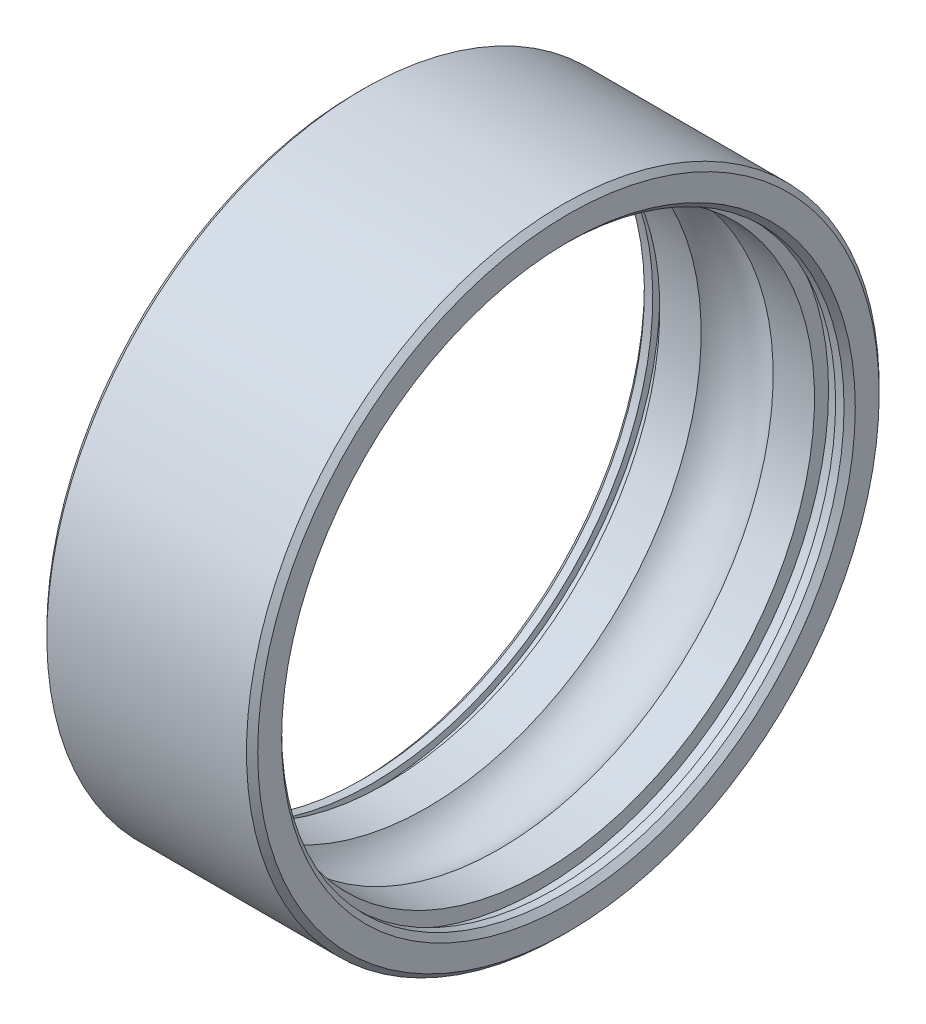
SolidWorks part; units mm, degrees
ref_plane "Front" through (0, 0, 0) normal (0, 0, 1) x (1, 0, 0)
ref_plane "Top" through (0, 0, 0) normal (0, 1, 0) x (1, 0, 0)
ref_plane "Right" through (0, 0, 0) normal (1, 0, 0) x (0, 0, -1)
sketch "Sketch1" plane through (0, 0, 0) normal (0, 0, 1) x (1, 0, 0)
  line L0 (-6.429, 0) -> (6.429, 0) construction
  line L1 (-1.5, -2.5) -> (1.5, -2.5) construction
  line L2 (-1.1, -3.9) -> (-0.5123, -3.9)
  line L3 (-1.5, -4) -> (-1.5, -4.5)
  line L4 (-1.5, -4.5) -> (1.5, -4.5)
  line L5 (1.5, -4) -> (1.5, -4.5)
  line L6 (0, -2.5) -> (0, -4.5) construction
  line L7 (-1.5, -3.1) -> (1.5, -3.1) construction
  line L8 (-1.1, -3.9) -> (-1.1, -4.1)
  line L9 (-1.1, -4.1) -> (-1.3, -4.1)
  line L10 (-1.3, -4.1) -> (-1.3, -4)
  line L11 (-1.3, -4) -> (-1.5, -4)
  line L12 (1.3, -4) -> (1.5, -4)
  line L13 (1.3, -4.1) -> (1.3, -4)
  line L14 (1.1, -4.1) -> (1.3, -4.1)
  line L15 (1.1, -3.9) -> (1.1, -4.1)
  line L16 (0.5123, -3.9) -> (1.1, -3.9)
  circle A0 centre (0, -3.5) radius 0.65 construction
  arc A1 (-0.5123, -3.9) -> (0.5123, -3.9) centre (0, -3.5) ccw
  point P13 (0, -3.5)
  point P15 (-1.3, -4.05)
  point P26 (0, 0)
  point P30 (0, -3.1)
  dimension "D3" = 1.3
  dimension "D1" = 4.5
  dimension "D2" = 2.5
  dimension "D4" = 0.6
  dimension "D5" = 3
  dimension "D6" = 0.4
  dimension "D7" = 0.1
  dimension "D8" = 0.1
  dimension "D9" = 0.2
  dimension "D10" = 0.6
  dimension "D11" = 3
revolve "Revolve1" add sketch "Sketch1" angle 360 about L0
chamfer "Chamfer1" distance 0.08 angle 45 4 edges at (1.5, -4, 0) (-1.5, -4, 0) (1.5, -4.5, 0) (-1.5, -4.5, 0)
